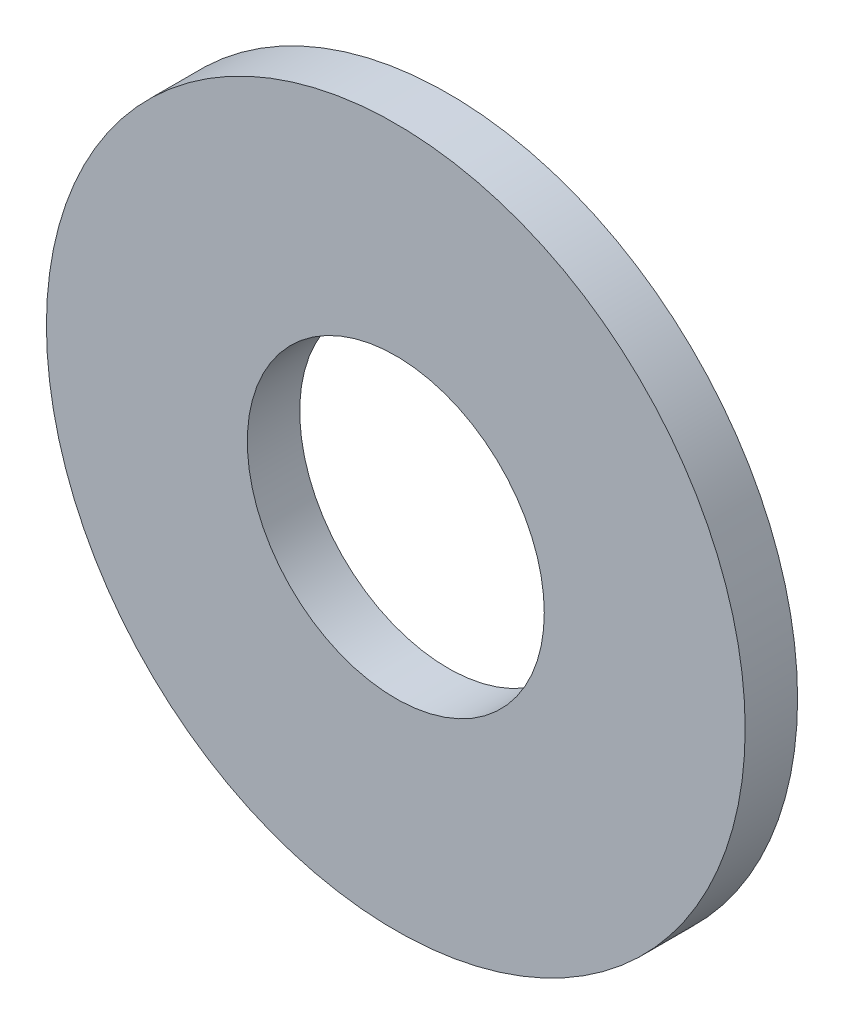
SolidWorks part; units mm, degrees
ref_plane "Спереди" through (0, 0, 0) normal (0, 0, 1) x (1, 0, 0)
ref_plane "Сверху" through (0, 0, 0) normal (0, 1, 0) x (1, 0, 0)
ref_plane "Справа" through (0, 0, 0) normal (1, 0, 0) x (0, 0, -1)
sketch "Эскиз1" plane through (0, 0, 0) normal (0, 0, 1) x (1, 0, 0)
  circle A0 centre (0, 0) radius 2
  dimension "d2" = 4
extrude "Основание-Вытянуть" add sketch "Эскиз1" along normal blind 0.3
sketch "Эскиз2" plane through (0, 0, 0.3) normal (0, 0, 1) x (1, 0, 0)
  circle A0 centre (0, 0) radius 0.85
  dimension "d1" = 1.7
extrude "Вырез-Вытянуть1" cut sketch "Эскиз2" against normal through all
